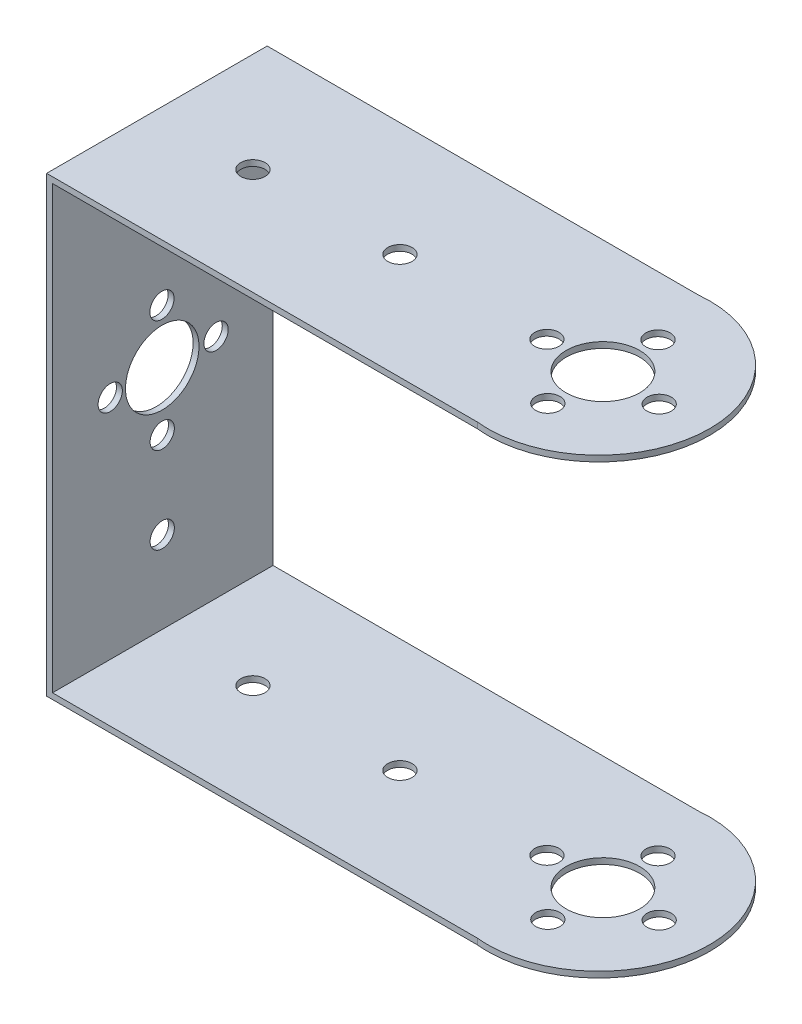
SolidWorks part; units mm, degrees
ref_plane "Front Plane" through (0, 0, 0) normal (0, 0, 1) x (1, 0, 0)
ref_plane "Top Plane" through (0, 0, 0) normal (0, 1, 0) x (1, 0, 0)
ref_plane "Right Plane" through (0, 0, 0) normal (1, 0, 0) x (0, 0, -1)
sketch "Sketch1" plane through (0, 0, 0) normal (0, 1, 0) x (1, 0, 0)
  line L1 (-39.505, -3.8119) -> (20.495, -3.8119)
  line L2 (-39.505, -3.8119) -> (-39.505, -33.8119)
  line L3 (-39.505, -33.8119) -> (20.495, -33.8119)
  line L4 (20.495, -3.8119) -> (20.495, -33.8119)
  dimension "D1" = 30
  dimension "D2" = 60
extrude "Boss-Extrude3" add sketch "Sketch1" along normal blind 0.8
sketch "Sketch4" plane through (0, 0, 0) normal (0, -1, 0) x (-1, 0, 0)
  line L0 (39.505, -3.8119) -> (39.505, -33.8119) construction
  line L1 (39.505, -33.8119) -> (38.705, -33.8119)
  line L2 (39.505, -33.8119) -> (39.505, -3.8119)
  line L3 (39.505, -3.8119) -> (38.705, -3.8119)
  line L4 (38.705, -33.8119) -> (38.705, -3.8119)
  line L5 (39.505, -33.8119) -> (-20.495, -33.8119) construction
  line L6 (-20.495, -3.8119) -> (39.505, -3.8119) construction
  dimension "D1" = 0.8
extrude "Boss-Extrude5" add sketch "Sketch4" along normal blind 30
sketch "Sketch5" plane through (0, 0, 0) normal (0, -1, 0) x (-1, 0, 0)
  line L0 (-20.6272, -3.8119) -> (-20.6272, -33.8119)
  line L1 (38.705, -33.8119) -> (-20.495, -33.8119) construction
  line L2 (-20.495, -3.8119) -> (38.705, -3.8119) construction
  ellipse E0 centre (-20.6272, -18.8119) end of major axis (-16.3413, -33.2666) minor radius 15.0457
extrude "Boss-Extrude6" add sketch "Sketch5" against normal blind 0.8
sketch "Sketch6" plane through (0, 0, 0) normal (0, -1, 0) x (-1, 0, 0)
  circle A0 centre (-21.6943, -19.3373) radius 5
  circle A1 centre (-21.6943, -26.827) radius 1.65
  circle A2 centre (-29.3496, -19.3373) radius 1.65
  circle A3 centre (-21.6943, -11.8413) radius 1.65
  circle A4 centre (-14.0798, -19.3373) radius 1.65
  circle A5 centre (5.9202, -19.3373) radius 1.65
  circle A6 centre (25.9202, -19.3373) radius 1.65
  circle A7 centre (-30.2617, -582.329) radius 5
  circle A8 centre (-37.917, -582.329) radius 1.65
  circle A9 centre (-30.2617, -574.8329) radius 1.65
  circle A10 centre (-22.6472, -582.329) radius 1.65
  circle A11 centre (-2.6472, -582.329) radius 1.65
  circle A12 centre (17.3528, -582.329) radius 1.65
  dimension "D1" = 10
  dimension "D2" = 3.3
  dimension "D3" = 3.3
  dimension "D4" = 3.3
  dimension "D5" = 3.3
  dimension "D6" = 3
  dimension "D7" = 3.3
extrude "Cut-Extrude2" cut sketch "Sketch6" against normal blind 10
mirror "Mirror1" about plane through (0, -30, 0) normal (0, -1, 0) of bodies 110
sketch "Sketch7" plane through (-38.705, 0, 0) normal (1, 0, 0) x (0, 0, -1)
  circle A0 centre (-18.8862, -29.1457) radius 5
  circle A1 centre (-18.9283, -21.7861) radius 1.65
  circle A2 centre (-11.5682, -29.1457) radius 1.65
  circle A3 centre (-18.8862, -37.099) radius 1.65
  circle A4 centre (-25.9622, -29.1457) radius 1.65
  circle A5 centre (-18.9283, -8.6704) radius 1.65
  circle A6 centre (-18.8862, -48.8352) radius 1.65
  dimension "D1" = 10
  dimension "D2" = 3.3
  dimension "D3" = 3.3
  dimension "D4" = 3.3
  dimension "D5" = 3.3
  dimension "D6" = 3.3
  dimension "D7" = 3.3
extrude "Cut-Extrude3" cut sketch "Sketch7" against normal blind 10
